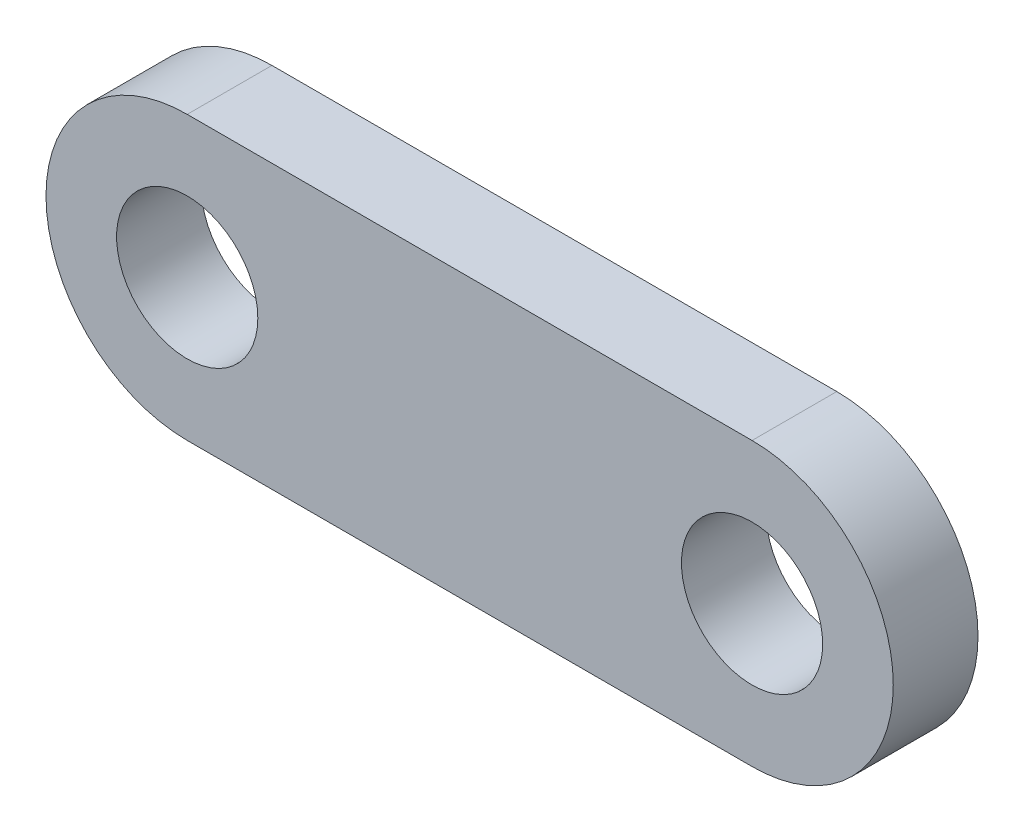
SolidWorks part; units mm, degrees
ref_plane "Front Plane" through (0, 0, 0) normal (0, 0, 1) x (1, 0, 0)
ref_plane "Top Plane" through (0, 0, 0) normal (0, 1, 0) x (1, 0, 0)
ref_plane "Right Plane" through (0, 0, 0) normal (1, 0, 0) x (0, 0, -1)
sketch "Sketch1" plane through (0, 0, 0) normal (0, 0, 1) x (1, 0, 0)
  line L0 (0, 0) -> (-20, 0) construction
  line L1 (0, -5) -> (-20, -5)
  line L2 (0, 5) -> (-20, 5)
  arc A0 (0, -5) -> (0, 5) centre (0, 0) ccw
  arc A1 (-20, 5) -> (-20, -5) centre (-20, 0) ccw
  circle A2 centre (-20, 0) radius 2.5
  circle A3 centre (0, 0) radius 2.5
  point P3 (-10, 0)
  dimension "D2" = 5
  dimension "D3" = 5
  dimension "D4" = 5
  dimension "D1" = 20
extrude "Boss-Extrude1" add sketch "Sketch1" along normal blind 3
